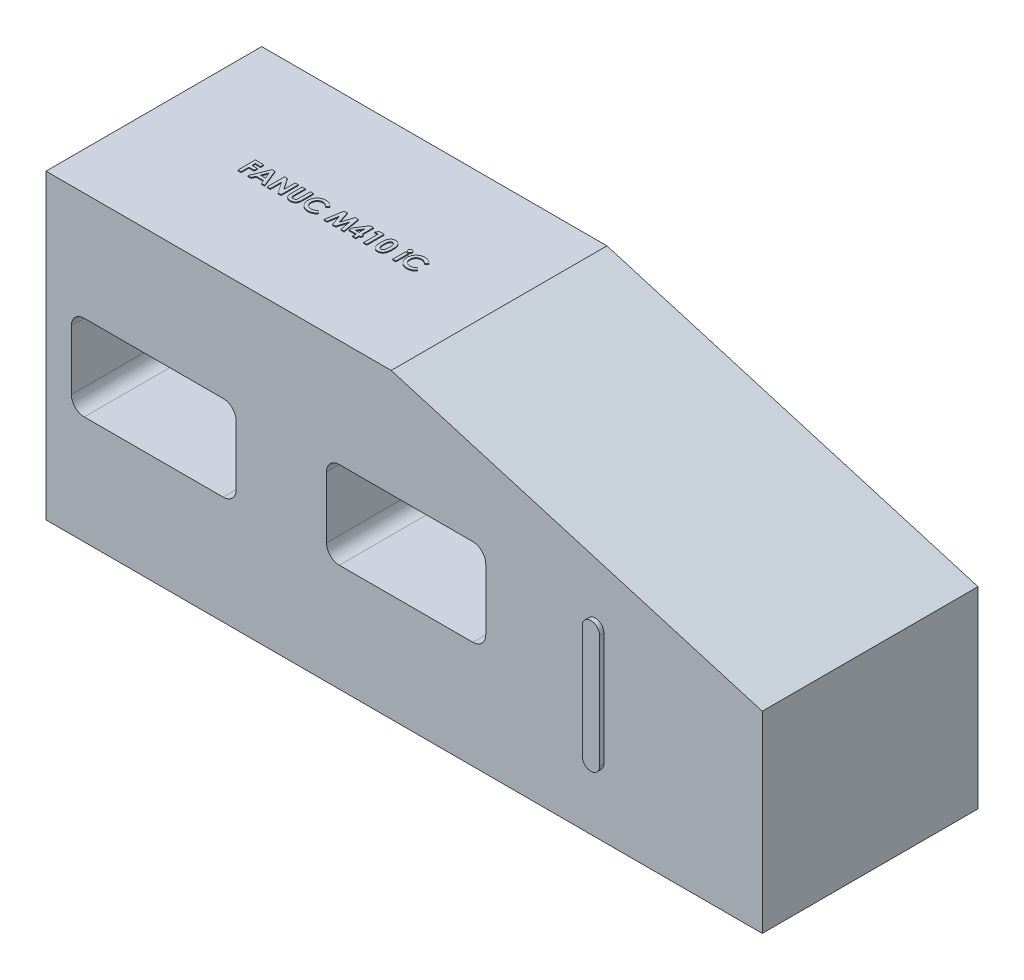
SolidWorks part; units mm, degrees
ref_plane "Front Plane" through (0, 0, 0) normal (0, 0, 1) x (1, 0, 0)
ref_plane "Top Plane" through (0, 0, 0) normal (0, 1, 0) x (1, 0, 0)
ref_plane "Right Plane" through (0, 0, 0) normal (1, 0, 0) x (0, 0, -1)
sketch "Sketch1" plane through (0, 0, 0) normal (0, 1, 0) x (1, 0, 0)
  line L1 (0, 0) -> (-400, 0)
  line L2 (0, 0) -> (0, 250)
  line L3 (0, 250) -> (-400, 250)
  line L4 (-400, 0) -> (-400, 250)
  dimension "D1" = 400
  dimension "D2" = 250
extrude "Boss-Extrude1" add sketch "Sketch1" against normal blind 350
sketch "Sketch2" plane through (0, 0, 0) normal (0, 0, 1) x (1, 0, 0)
  line L0 (0, 0) -> (430, -127)
  line L1 (430, -127) -> (430, -350)
  line L2 (430, -350) -> (0, -350)
  line L3 (0, 0) -> (0, -350)
  dimension "D1" = 223
  dimension "D2" = 430
extrude "Boss-Extrude2" add sketch "Sketch2" against normal blind 250
sketch "Sketch3" plane through (0, 0, 0) normal (0, 0, 1) x (1, 0, 0)
  line L0 (236.4782, -140.2735) -> (236.4782, -271.5848) construction
  line L1 (246.4782, -140.2735) -> (246.4782, -271.5848)
  line L2 (226.4782, -140.2735) -> (226.4782, -271.5848)
  arc A0 (246.4782, -140.2735) -> (226.4782, -140.2735) centre (236.4782, -140.2735) ccw
  arc A1 (226.4782, -271.5848) -> (246.4782, -271.5848) centre (236.4782, -271.5848) ccw
  point P2 (236.4782, -205.9292)
extrude "Boss-Extrude3" add sketch "Sketch3" along normal blind 5
sketch "Sketch4" plane through (0, 0, 0) normal (0, 0, 1) x (1, 0, 0)
  line L0 (-400, -175) -> (882.6911, -175) construction
  line L1 (-355.6097, -125.4975) -> (-194.6796, -125.4975)
  line L2 (-370.6097, -140.4975) -> (-370.6097, -209.5025)
  line L3 (-355.6097, -224.5025) -> (-194.6796, -224.5025)
  line L4 (-179.6796, -140.4975) -> (-179.6796, -209.5025)
  line L5 (-60.0398, -124.4995) -> (94.5842, -124.4995)
  line L6 (-75.0398, -139.4995) -> (-75.0398, -210.5005)
  line L7 (-60.0398, -225.5005) -> (94.5842, -225.5005)
  line L8 (109.5842, -139.4995) -> (109.5842, -210.5005)
  line L9 (-400, -350) -> (-400, 0) construction
  arc A0 (-75.0398, -210.5005) -> (-60.0398, -225.5005) centre (-60.0398, -210.5005) ccw
  arc A1 (94.5842, -225.5005) -> (109.5842, -210.5005) centre (94.5842, -210.5005) ccw
  arc A2 (94.5842, -124.4995) -> (109.5842, -139.4995) centre (94.5842, -139.4995) cw
  arc A3 (-60.0398, -124.4995) -> (-75.0398, -139.4995) centre (-60.0398, -139.4995) ccw
  arc A4 (-194.6796, -224.5025) -> (-179.6796, -209.5025) centre (-194.6796, -209.5025) ccw
  arc A5 (-370.6097, -209.5025) -> (-355.6097, -224.5025) centre (-355.6097, -209.5025) ccw
  arc A6 (-194.6796, -125.4975) -> (-179.6796, -140.4975) centre (-194.6796, -140.4975) cw
  arc A7 (-355.6097, -125.4975) -> (-370.6097, -140.4975) centre (-355.6097, -140.4975) ccw
  dimension "D1" = 15
extrude "Cut-Extrude1" cut sketch "Sketch4" against normal blind 490
sketch "Sketch6" plane through (0, 0, 0) normal (0, 1, 0) x (1, 0, 0)
  text T0 "<b>FANUC M410 iC</b>" font "Century Gothic" height 20
  point P1 (0, 0)
extrude "Boss-Extrude4" add sketch "Sketch6" along normal blind 1
